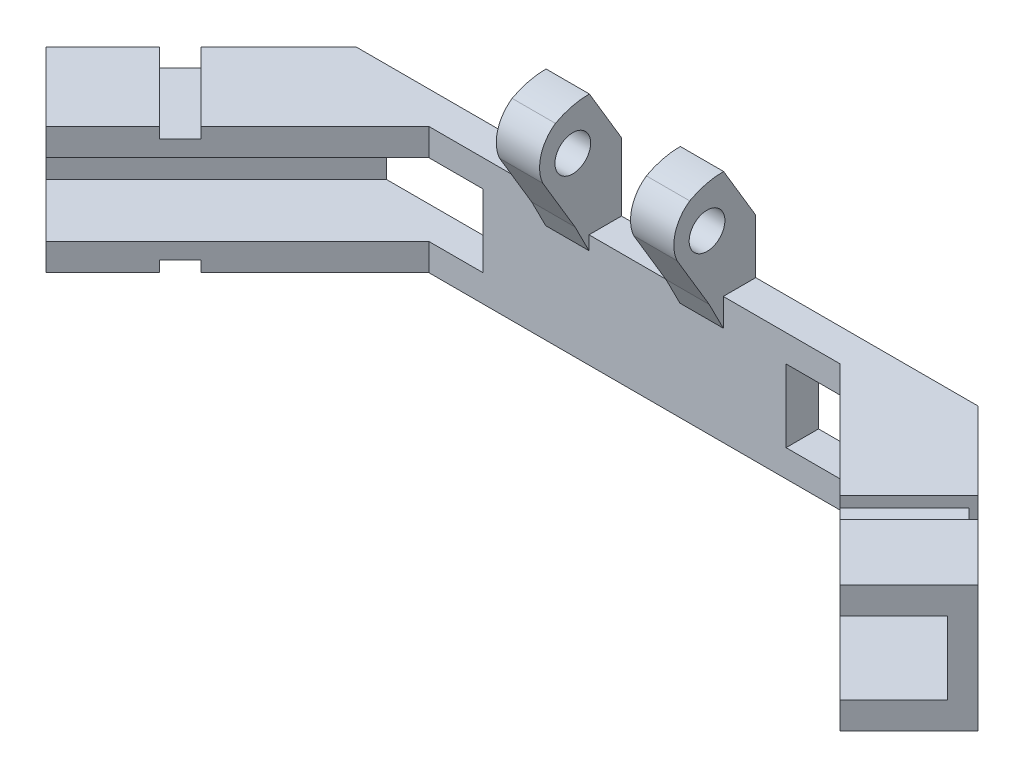
SolidWorks part; units mm, degrees
ref_plane "Alzado" through (0, 0, 0) normal (0, 0, 1) x (1, 0, 0)
ref_plane "Planta" through (0, 0, 0) normal (0, 1, 0) x (1, 0, 0)
ref_plane "Vista lateral" through (0, 0, 0) normal (1, 0, 0) x (0, 0, -1)
sketch "Croquis1" plane through (0, 0, 0) normal (0, 0, 1) x (1, 0, 0)
  line L1 (-79.7009, 22.7196) -> (8.2991, 22.7196)
  line L2 (-79.7009, 22.7196) -> (-79.7009, 11.0196)
  line L3 (-79.7009, 11.0196) -> (8.2991, 11.0196)
  line L4 (8.2991, 22.7196) -> (8.2991, 11.0196)
  dimension "D1" = 88
  dimension "D2" = 11.7
extrude "Saliente-Extruir1" add sketch "Croquis1" along normal blind 25
sketch "Croquis3" plane through (0, 11.0196, 0) normal (0, -1, 0) x (1, 0, 0)
  line L0 (-16.7009, 3) -> (0.9767, 20.6777)
  line L1 (-79.7009, 0) -> (8.2991, 0) construction
  line L3 (-54.7009, 3) -> (-16.7009, 3)
  line L4 (-54.7009, 3) -> (-72.3786, 20.6777)
  line L5 (0.9767, 20.6777) -> (7.3407, 14.3137)
  line L6 (7.3407, 14.3137) -> (-6.973, 0)
  line L7 (-72.3786, 20.6777) -> (-78.7426, 14.3137)
  line L8 (-78.7426, 14.3137) -> (-64.4289, 0)
  line L9 (-64.4289, 0) -> (-79.7009, 0)
  line L10 (-79.7009, 0) -> (-79.7009, 25)
  line L11 (-79.7009, 25) -> (8.2991, 25)
  line L12 (8.2991, 25) -> (8.2991, 0)
  line L13 (8.2991, 0) -> (-6.973, 0)
  dimension "D2" = 3
extrude "Cortar-Extruir1" cut sketch "Croquis3" against normal up to vertex (11.7 mm away)
sketch "Croquis4" plane through (-46.5281, 0, 46.5281) normal (-0.7071, 0, 0.7071) x (0.7071, 0, 0.7071)
  line L0 (-36.5581, 22.7196) -> (-36.5581, 11.0196) construction
  line L1 (-36.5581, 20.2196) -> (-43.5581, 20.2196)
  line L2 (-36.5581, 20.2196) -> (-36.5581, 13.5196)
  line L3 (-36.5581, 13.5196) -> (-43.5581, 13.5196)
  line L4 (-43.5581, 20.2196) -> (-43.5581, 13.5196)
  line L5 (-45.5581, 22.7196) -> (-36.5581, 22.7196) construction
  line L7 (-45.5581, 22.7196) -> (-45.5581, 11.0196) construction
  dimension "D1" = 2.5
  dimension "D2" = 6.7
  dimension "D3" = 2
  dimension "D4" = 7
extrude "Cortar-Extruir2" cut sketch "Croquis4" against normal blind 30
sketch "Croquis5" plane through (10.8272, 0, 10.8272) normal (0.7071, 0, 0.7071) x (0.7071, 0, -0.7071)
  line L0 (-13.9307, 22.7196) -> (-13.9307, 11.0196) construction
  line L1 (-13.9307, 13.5196) -> (-6.9307, 13.5196)
  line L2 (-13.9307, 13.5196) -> (-13.9307, 20.2196)
  line L3 (-13.9307, 20.2196) -> (-6.9307, 20.2196)
  line L4 (-6.9307, 13.5196) -> (-6.9307, 20.2196)
  line L6 (-13.9307, 11.0196) -> (-4.9307, 11.0196) construction
  line L7 (-4.9307, 22.7196) -> (-4.9307, 11.0196) construction
  dimension "D1" = 2.5
  dimension "D2" = 6.7
  dimension "D3" = 2
extrude "Cortar-Extruir3" cut sketch "Croquis5" against normal blind 30
sketch "Croquis6" plane through (0, 0, 3) normal (0, 0, 1) x (1, 0, 0)
  line L1 (-54.7009, 13.5196) -> (-49.7009, 13.5196)
  line L2 (-54.7009, 13.5196) -> (-54.7009, 20.2196)
  line L3 (-54.7009, 20.2196) -> (-49.7009, 20.2196)
  line L4 (-49.7009, 13.5196) -> (-49.7009, 20.2196)
  line L5 (-16.7009, 20.2196) -> (-21.7009, 20.2196)
  line L6 (-16.7009, 20.2196) -> (-16.7009, 13.5196)
  line L7 (-16.7009, 13.5196) -> (-21.7009, 13.5196)
  line L8 (-21.7009, 20.2196) -> (-21.7009, 13.5196)
  dimension "D1" = 5
  dimension "D2" = 5
extrude "Cortar-Extruir4" cut sketch "Croquis6" against normal up to vertex (3 mm away)
sketch "Croquis7" plane through (-3.4865, 0, 3.4865) normal (0.7071, 0, -0.7071) x (-0.7071, 0, -0.7071)
  line L0 (-15.312, 11.0196) -> (4.9307, 11.0196) construction
  line L1 (-5.1907, 11.0196) -> (-7.8907, 11.0196)
  line L2 (-5.1907, 11.0196) -> (-5.1907, 12.0196)
  line L3 (-5.1907, 12.0196) -> (-7.8907, 12.0196)
  line L4 (-7.8907, 11.0196) -> (-7.8907, 12.0196)
  line L5 (-15.312, 22.7196) -> (4.9307, 22.7196) construction
  line L6 (-5.1907, 22.7196) -> (-7.8907, 22.7196)
  line L7 (-5.1907, 22.7196) -> (-5.1907, 21.7196)
  line L8 (-5.1907, 21.7196) -> (-7.8907, 21.7196)
  line L9 (-7.8907, 22.7196) -> (-7.8907, 21.7196)
  dimension "D1" = 1
  dimension "D2" = 2.7
  dimension "D3" = 2.7
  dimension "D4" = 1
extrude "Cortar-Extruir5" cut sketch "Croquis7" against normal blind 30
sketch "Croquis9" plane through (0, 12.0196, 0) normal (0, -1, 0) x (1, 0, 0)
  line L0 (0.1838, 7.1569) -> (2.093, 9.066)
  line L1 (2.093, 9.066) -> (1.6722, 9.4868)
  line L2 (-4.2709, 15.43) -> (2.093, 9.066) construction
  line L3 (1.6722, 9.4868) -> (-0.237, 7.5777)
  line L4 (-6.1801, 13.5208) -> (0.1838, 7.1569) construction
  line L5 (-0.237, 7.5777) -> (0.1838, 7.1569)
extrude "Cortar-Extruir6" cut sketch "Croquis9" against normal blind 30
sketch "Croquis10" plane through (-32.2144, 0, -32.2144) normal (-0.7071, 0, -0.7071) x (-0.7071, 0, 0.7071)
  line L0 (45.5581, 22.7196) -> (65.8007, 22.7196) construction
  line L1 (55.6794, 22.7196) -> (58.3794, 22.7196)
  line L2 (55.6794, 22.7196) -> (55.6794, 21.7196)
  line L3 (55.6794, 21.7196) -> (58.3794, 21.7196)
  line L4 (58.3794, 22.7196) -> (58.3794, 21.7196)
  line L5 (45.5581, 11.0196) -> (65.8007, 11.0196) construction
  line L6 (55.6794, 11.0196) -> (58.3794, 11.0196)
  line L7 (55.6794, 11.0196) -> (55.6794, 12.0196)
  line L8 (55.6794, 12.0196) -> (58.3794, 12.0196)
  line L9 (58.3794, 11.0196) -> (58.3794, 12.0196)
  dimension "D1" = 1
  dimension "D2" = 1
  dimension "D3" = 2.7
  dimension "D4" = 2.7
extrude "Cortar-Extruir7" cut sketch "Croquis10" against normal blind 30
sketch "Croquis11" plane through (0, 12.0196, 0) normal (0, -1, 0) x (1, 0, 0)
  line L0 (-71.5857, 7.1569) -> (-70.8786, 7.864)
  line L1 (-65.2217, 13.5208) -> (-71.5857, 7.1569) construction
  line L2 (-70.8786, 7.864) -> (-72.7878, 9.7731)
  line L3 (-67.1309, 15.43) -> (-73.4949, 9.066) construction
  line L4 (-72.7878, 9.7731) -> (-73.4949, 9.066)
  line L5 (-73.4949, 9.066) -> (-71.5857, 7.1569)
extrude "Cortar-Extruir8" cut sketch "Croquis11" against normal blind 30
sketch "Croquis12" plane through (0, 22.7196, 0) normal (0, 1, 0) x (1, 0, 0)
  line L2 (-6.973, 0) -> (-64.4289, 0) construction
  line L4 (-27.5009, 0) -> (-31.5009, 0)
  line L5 (-27.5009, 0) -> (-27.5009, -8.5)
  line L6 (-27.5009, -8.5) -> (-31.5009, -8.5)
  line L7 (-31.5009, 0) -> (-31.5009, -8.5)
  line L8 (-39.9009, 0) -> (-43.9009, 0)
  line L9 (-39.9009, 0) -> (-39.9009, -8.5)
  line L10 (-39.9009, -8.5) -> (-43.9009, -8.5)
  line L11 (-43.9009, 0) -> (-43.9009, -8.5)
  dimension "D1" = 4
  dimension "D2" = 8.5
  dimension "D3" = 8.4
  dimension "D4" = 4
  dimension "D5" = 8.5
extrude "Saliente-Extruir2" add sketch "Croquis12" along normal blind 10
sketch "Croquis13" plane through (-27.5009, 0, 0) normal (1, 0, 0) x (0, 0, -1)
  line L2 (0, 27.7196) -> (-2.9715, 32.6999)
  line L4 (-4.2927, 22.7196) -> (-8.4694, 29.7197)
  line L6 (-8.5, 22.7196) -> (-3, 22.7196) construction
  line L7 (-4.2927, 22.7196) -> (-8.5, 22.7196)
  line L9 (0, 32.7196) -> (0, 22.7196) construction
  line L10 (0, 27.7196) -> (0, 32.7196)
  line L11 (-8.5, 32.7196) -> (0, 32.7196)
  line L12 (-8.5, 22.7196) -> (-8.5, 32.7196)
  circle A0 centre (-4.5, 28.7196) radius 1.65
  arc A1 (-8.4694, 29.7197) -> (-2.9715, 32.6999) centre (-2.9904, 26.1735) cw
extrude "Cortar-Extruir9" cut sketch "Croquis13" against normal up to vertex
sketch "Croquis14" plane through (-27.5009, 0, 0) normal (1, 0, 0) x (0, 0, -1)
  line L0 (-4.2927, 22.7196) -> (-8.4694, 29.7197) construction
  line L1 (-7.2692, 27.7083) -> (-8.4694, 29.7197)
  line L2 (-8.4694, 29.7197) -> (-7.5483, 31.8156)
  line L3 (-7.5483, 31.8156) -> (-6.1006, 31.9112)
  arc A0 (-7.2692, 27.7083) -> (-6.1006, 31.9112) centre (-4.139, 29.1018) cw
  arc A1 (-2.9715, 32.6999) -> (-8.4694, 29.7197) centre (-2.9904, 26.1735) ccw construction
  line M3 (-8.4694, 29.7197) -> (-4.2927, 22.7196)
extrude "Cortar-Extruir10" cut sketch "Croquis14" against normal blind 20 contours A0 L3 L2 M3
sketch "Croquis15" plane through (0, 0, 3) normal (0, 0, 1) x (1, 0, 0)
  line L1 (-43.9009, 22.7196) -> (-39.9009, 22.7196)
  line L2 (-43.9009, 22.7196) -> (-43.9009, 16.9296)
  line L3 (-43.9009, 16.9296) -> (-39.9009, 16.9296)
  line L4 (-39.9009, 22.7196) -> (-39.9009, 16.9296)
  line L5 (-31.5009, 22.7196) -> (-27.5009, 22.7196)
  line L6 (-31.5009, 22.7196) -> (-31.5009, 16.9296)
  line L7 (-31.5009, 16.9296) -> (-27.5009, 16.9296)
  line L8 (-27.5009, 22.7196) -> (-27.5009, 16.9296)
extrude "Saliente-Extruir3" add sketch "Croquis15" along normal up to vertex (1.2927 mm away)
sketch "Croquis16" plane through (-43.9009, 0, 0) normal (-1, 0, 0) x (0, 0, 1)
  line L0 (4.2927, 22.7196) -> (3, 20.1756)
  line L2 (3, 22.7196) -> (3, 16.9296) construction
  line L3 (3, 20.1756) -> (3, 16.9296)
  line L4 (3, 16.9296) -> (4.2927, 16.9296)
  line L5 (4.2927, 16.9296) -> (4.2927, 22.7196)
extrude "Cortar-Extruir11" cut sketch "Croquis16" against normal up to vertex
sketch "Croquis17" plane through (0, 0, 3) normal (0, 0, 1) x (1, 0, 0)
  line L0 (-31.5009, 22.7196) -> (-31.5009, 20.1756) construction
  line L1 (-39.9009, 22.7196) -> (-31.5009, 22.7196)
  line L2 (-39.9009, 22.7196) -> (-39.9009, 21.4476)
  line L3 (-39.9009, 21.4476) -> (-31.5009, 21.4476)
  line L4 (-31.5009, 22.7196) -> (-31.5009, 21.4476)
extrude "Cortar-Extruir12" cut sketch "Croquis17" against normal blind 20
